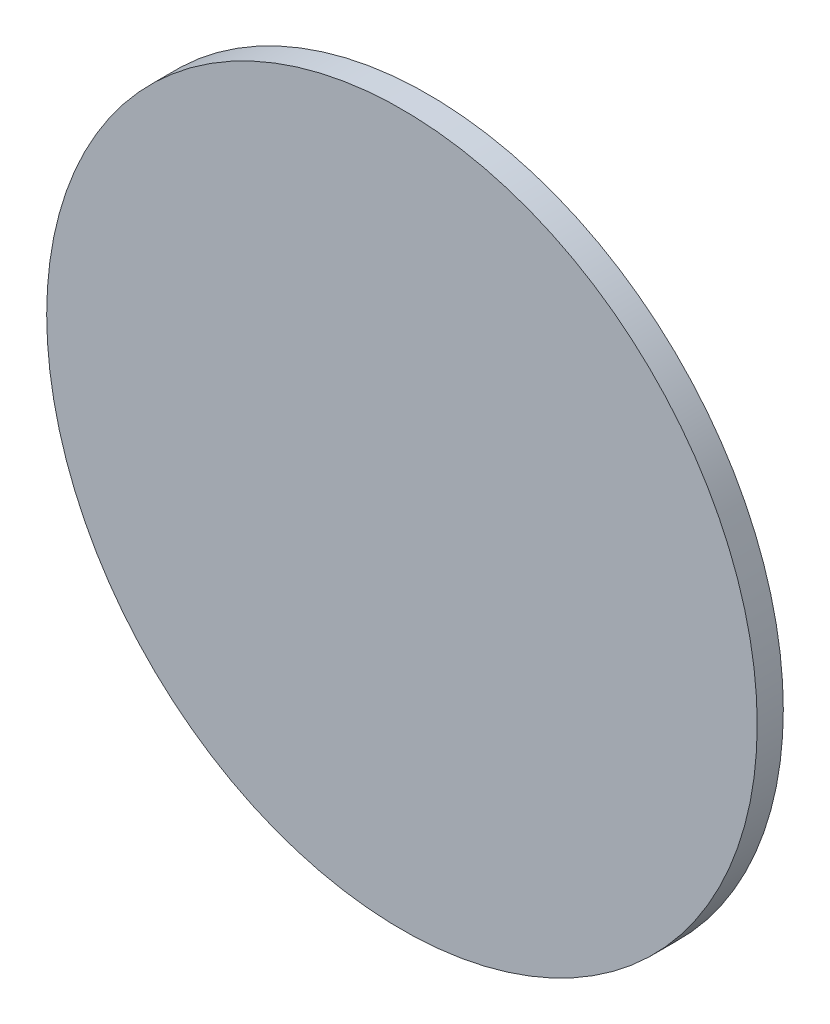
SolidWorks part; units mm, degrees
ref_plane "Front Plane" through (0, 0, 0) normal (0, 0, 1) x (1, 0, 0)
ref_plane "Top Plane" through (0, 0, 0) normal (0, 1, 0) x (1, 0, 0)
ref_plane "Right Plane" through (0, 0, 0) normal (1, 0, 0) x (0, 0, -1)
sketch "Sketch1" plane through (0, 0, 0) normal (0, 0, 1) x (1, 0, 0)
  circle A0 centre (-114.9635, 311.5884) radius 27.2332
extrude "Boss-Extrude1" add sketch "Sketch1" along normal blind 2
